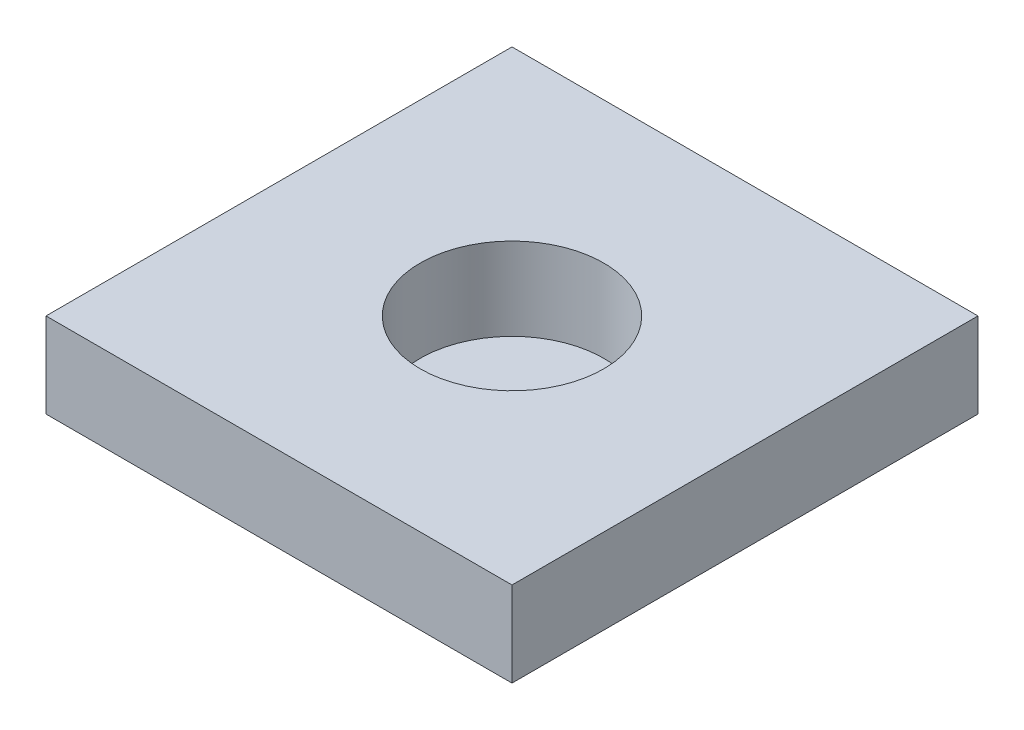
SolidWorks part; units mm, degrees
ref_plane "Front Plane" through (0, 0, 0) normal (0, 0, 1) x (1, 0, 0)
ref_plane "Top Plane" through (0, 0, 0) normal (0, 1, 0) x (1, 0, 0)
ref_plane "Right Plane" through (0, 0, 0) normal (1, 0, 0) x (0, 0, -1)
sketch "Sketch1" plane through (0, 0, 0) normal (0, 1, 0) x (1, 0, 0)
  line L1 (0, 0) -> (152.4, 0)
  line L2 (0, 0) -> (0, 152.4)
  line L3 (0, 152.4) -> (152.4, 152.4)
  line L4 (152.4, 0) -> (152.4, 152.4)
  dimension "D1" = 152.4
  dimension "D2" = 152.4
extrude "Boss-Extrude1" add sketch "Sketch1" along normal blind 0.8 contours L2 L3 L4 L1
sketch "Sketch2" plane through (0, 0.8, 0) normal (0, 1, 0) x (1, 0, 0)
  line L0 (0, 76.2) -> (152.4, 76.2) construction
  line L1 (0, 0) -> (0, 152.4) construction
  line L2 (152.4, 0) -> (152.4, 152.4) construction
  circle A0 centre (76.2, 76.2) radius 5.25
  dimension "D1" = 10.5
extrude "Cut-Extrude2" cut sketch "Sketch2" against normal blind 254 contours A0
sketch "Sketch3" plane through (0, 0.8, 0) normal (0, 1, 0) x (1, 0, 0)
  line L1 (0, 152.4) -> (152.4, 152.4)
  line L2 (0, 152.4) -> (0, 0)
  line L3 (0, 0) -> (152.4, 0)
  line L4 (152.4, 152.4) -> (152.4, 0)
extrude "Boss-Extrude2" add sketch "Sketch3" along normal blind 27
sketch "Sketch4" plane through (0, 27.8, 0) normal (0, 1, 0) x (1, 0, 0)
  line L0 (0, 76.2) -> (152.4, 76.2) construction
  line L1 (0, 152.4) -> (0, 0) construction
  line L2 (152.4, 0) -> (152.4, 152.4) construction
  circle A0 centre (76.2, 76.2) radius 30
  dimension "D1" = 60
extrude "Cut-Extrude3" cut sketch "Sketch4" against normal blind 27
